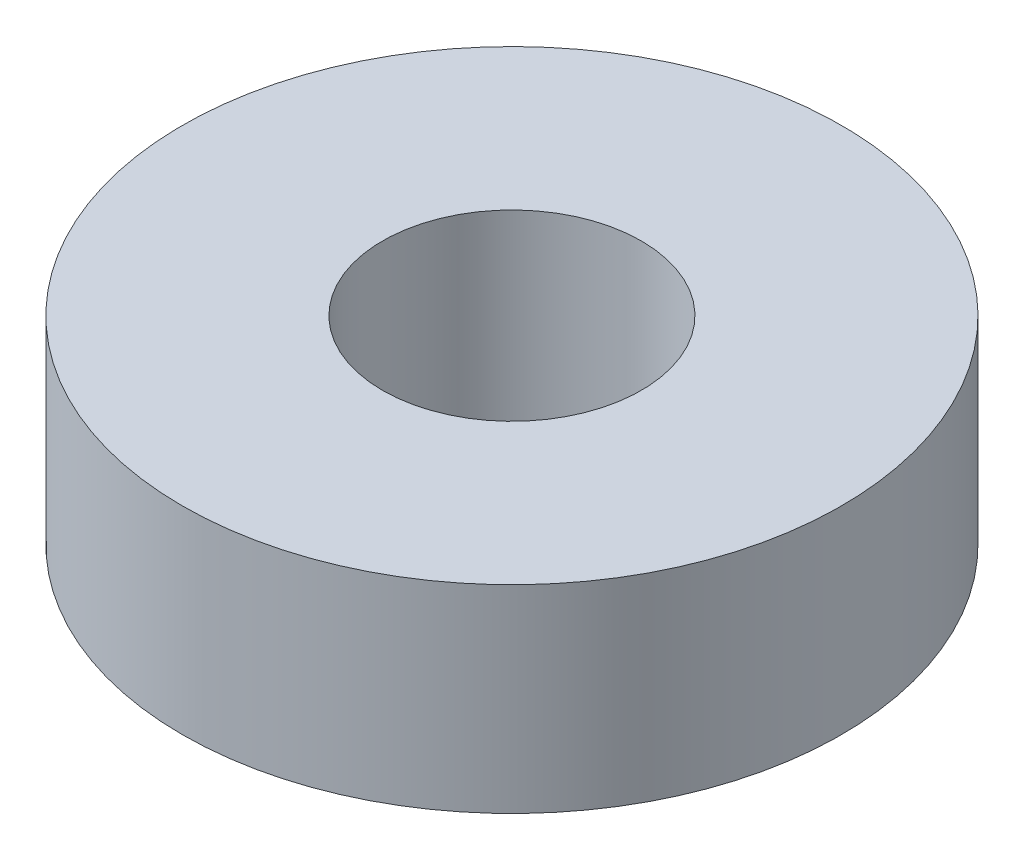
SolidWorks part; units mm, degrees
ref_plane "Front Plane" through (0, 0, 0) normal (0, 0, 1) x (1, 0, 0)
ref_plane "Top Plane" through (0, 0, 0) normal (0, 1, 0) x (1, 0, 0)
ref_plane "Right Plane" through (0, 0, 0) normal (1, 0, 0) x (0, 0, -1)
sketch "Sketch1" plane through (0, 0, 0) normal (0, 1, 0) x (1, 0, 0)
  circle A0 centre (0, 0) radius 9.9
  circle A1 centre (0, 0) radius 4
  dimension "D1" = 19.8
  dimension "D2" = 8
extrude "Boss-Extrude1" add sketch "Sketch1" along normal blind 6
other "Move Face1" face at (0, 6, 9.9) face at (0, 6, 4) parameters "D1"=0.08
